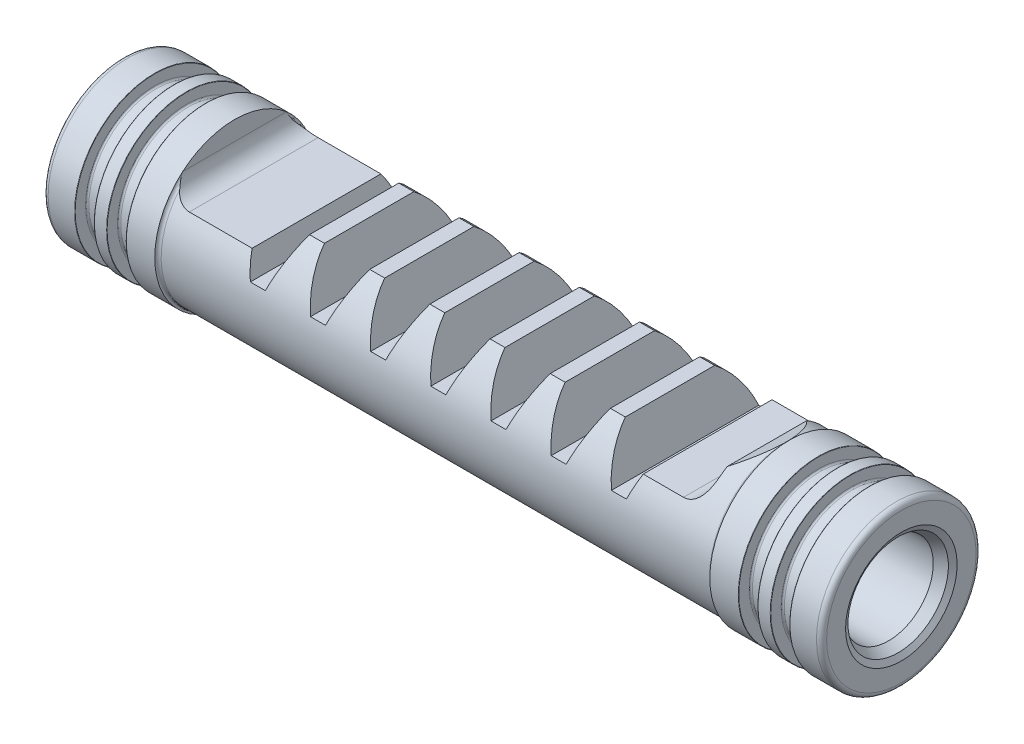
SolidWorks part; units mm, degrees
material "Простая углеродистая сталь"
ref_plane "Спереди" through (0, 0, 0) normal (0, 0, 1) x (1, 0, 0)
ref_plane "Сверху" through (0, 0, 0) normal (0, 1, 0) x (1, 0, 0)
ref_plane "Справа" through (0, 0, 0) normal (1, 0, 0) x (0, 0, -1)
sketch "Эскиз1" plane through (0, 0, 0) normal (0, 0, 1) x (1, 0, 0)
  line L0 (-137.6559, 0) -> (137.6559, 0) construction
  line L1 (-121.94, 17.4641) -> (-121.94, 23.4)
  line L2 (-120.34, 25) -> (-112.04, 25)
  line L3 (-111.94, 24.9) -> (-111.94, 21.65)
  line L4 (-111.44, 21.15) -> (-106.44, 21.15)
  line L5 (-105.94, 21.65) -> (-105.94, 24.9)
  line L6 (-105.84, 25) -> (-102.04, 25)
  line L7 (-101.94, 24.9) -> (-101.94, 21.65)
  line L8 (-101.44, 21.15) -> (-96.44, 21.15)
  line L9 (-95.94, 21.65) -> (-95.94, 24.9)
  line L10 (-95.84, 25) -> (-86.94, 25)
  line L11 (0, 34.36) -> (0, 0) construction
  line L12 (-121.94, 17.4641) -> (-120.94, 15.7321)
  line L13 (-120.94, 15.7321) -> (-117.94, 14)
  line L14 (-117.94, 14) -> (-93.94, 14)
  line L15 (-93.94, 14) -> (-85.8571, 0)
  line L16 (-85.8571, 0) -> (85.8571, 0)
  line L17 (-51.84, 25) -> (-51.84, 0) construction
  line L18 (51.84, 25) -> (51.84, 0) construction
  line L19 (93.94, 14) -> (85.8571, 0)
  line L20 (117.94, 14) -> (93.94, 14)
  line L21 (120.94, 15.7321) -> (117.94, 14)
  line L22 (121.94, 17.4641) -> (120.94, 15.7321)
  line L23 (95.94, 21.65) -> (95.94, 24.9)
  line L24 (101.44, 21.15) -> (96.44, 21.15)
  line L25 (101.94, 24.9) -> (101.94, 21.65)
  line L26 (105.84, 25) -> (102.04, 25)
  line L27 (105.94, 21.65) -> (105.94, 24.9)
  line L28 (111.44, 21.15) -> (106.44, 21.15)
  line L29 (111.94, 24.9) -> (111.94, 21.65)
  line L30 (120.34, 25) -> (112.04, 25)
  line L31 (121.94, 17.4641) -> (121.94, 23.4)
  line L32 (-85.94, 24) -> (85.94, 24)
  line L33 (86.94, 25) -> (95.84, 25)
  arc A0 (-95.94, 24.9) -> (-95.84, 25) centre (-95.84, 24.9) cw
  arc A1 (-102.04, 25) -> (-101.94, 24.9) centre (-102.04, 24.9) cw
  arc A2 (-105.94, 24.9) -> (-105.84, 25) centre (-105.84, 24.9) cw
  arc A3 (-112.04, 25) -> (-111.94, 24.9) centre (-112.04, 24.9) cw
  arc A4 (-96.44, 21.15) -> (-95.94, 21.65) centre (-96.44, 21.65) ccw
  arc A5 (-101.94, 21.65) -> (-101.44, 21.15) centre (-101.44, 21.65) ccw
  arc A6 (-106.44, 21.15) -> (-105.94, 21.65) centre (-106.44, 21.65) ccw
  arc A7 (-111.94, 21.65) -> (-111.44, 21.15) centre (-111.44, 21.65) ccw
  arc A8 (-121.94, 23.4) -> (-120.34, 25) centre (-120.34, 23.4) cw
  arc A9 (121.94, 23.4) -> (120.34, 25) centre (120.34, 23.4) ccw
  arc A10 (111.94, 21.65) -> (111.44, 21.15) centre (111.44, 21.65) cw
  arc A11 (106.44, 21.15) -> (105.94, 21.65) centre (106.44, 21.65) cw
  arc A12 (101.94, 21.65) -> (101.44, 21.15) centre (101.44, 21.65) cw
  arc A13 (96.44, 21.15) -> (95.94, 21.65) centre (96.44, 21.65) cw
  arc A14 (112.04, 25) -> (111.94, 24.9) centre (112.04, 24.9) ccw
  arc A15 (105.94, 24.9) -> (105.84, 25) centre (105.84, 24.9) ccw
  arc A16 (102.04, 25) -> (101.94, 24.9) centre (102.04, 24.9) ccw
  arc A17 (95.94, 24.9) -> (95.84, 25) centre (95.84, 24.9) ccw
  arc A18 (-85.94, 24) -> (-86.94, 25) centre (-85.94, 25) cw
  arc A19 (85.94, 24) -> (86.94, 25) centre (85.94, 25) ccw
  point P74 (0, 25)
  point P82 (0, 24)
  dimension "D3" = 0.1
  dimension "D4" = 0.5
  dimension "D5" = 1.6
  dimension "D19" = 1
  dimension "D1" = 6
  dimension "D2" = 6
  dimension "D6" = 60
  dimension "D7" = 28
  dimension "D8" = 60
  dimension "D9" = 28
  dimension "D10" = 30
  dimension "D11" = 4
  dimension "D12" = 1
  dimension "D13" = 70.1
  dimension "D14" = 103.68
  dimension "D15" = 50
  dimension "D16" = 42.3
  dimension "D17" = 10
  dimension "D18" = 20
  dimension "D20" = 48
  dimension "D21" = 35
revolve "Повернуть1" add sketch "Эскиз1" angle 360 about L0
sketch "Эскиз3" plane through (0, 0, 0) normal (0, 0, 1) x (1, 0, 0)
  line L0 (-86.94, 25) -> (-86.94, 19)
  line L1 (-80.94, 13) -> (-51.84, 13)
  line L2 (-51.84, 13) -> (-51.84, 19.5)
  line L3 (-51.84, 19.5) -> (51.84, 19.5)
  line L4 (51.84, 19.5) -> (51.84, 13)
  line L5 (51.84, 13) -> (73.8778, 13)
  line L6 (79.8778, 20.5) -> (85.94, 24)
  line L7 (85.94, 24) -> (-85.94, 24) construction
  line L8 (85.94, 24) -> (85.94, 25)
  line L9 (85.94, 25) -> (-86.94, 25)
  line L10 (79.8778, 20.5) -> (79.8778, 19)
  line L11 (-51.84, 25) -> (-51.84, 0) construction
  line L12 (51.84, 25) -> (51.84, 0) construction
  line L13 (-95.84, -25) -> (-86.94, -25) construction
  arc A0 (73.8778, 13) -> (79.8778, 19) centre (73.8778, 19) ccw
  arc A1 (-86.94, 19) -> (-80.94, 13) centre (-80.94, 19) ccw
  dimension "D2" = 12
  dimension "D4" = 6
  dimension "D1" = 3.5
  dimension "D3" = 44.5
  dimension "D5" = 30
extrude "Вырез-Вытянуть1" cut sketch "Эскиз3" against normal through all and the other way through all
sketch "Эскиз5" plane through (0, 0, 0) normal (0, 0, 1) x (1, 0, 0)
  line L0 (-48.3517, -24) -> (-39.64, -17.9)
  line L1 (-85.94, -24) -> (85.94, -24) construction
  line L2 (-39.64, -17.9) -> (-24.64, -17.9)
  line L3 (-24.64, -17.9) -> (-14.7491, -21.5)
  line L4 (-14.7491, -21.5) -> (91.94, -21.5)
  line L5 (91.94, -21.5) -> (91.94, -24)
  line L6 (86.94, -25) -> (95.84, -25) construction
  line L7 (92.94, -25) -> (-48.3517, -25)
  line L8 (-48.3517, -25) -> (-48.3517, -24)
  line L9 (-121.94, 23.4) -> (-121.94, -23.4) construction
  line L10 (121.94, -23.4) -> (121.94, 23.4) construction
  arc A0 (91.94, -24) -> (92.94, -25) centre (92.94, -24) ccw
  dimension "D8" = 1
  dimension "D1" = 35
  dimension "D2" = 3.6
  dimension "D3" = 7.1
  dimension "D4" = 15
  dimension "D5" = 20
  dimension "D6" = 97.3
  dimension "D7" = 30
extrude "Вырез-Вытянуть3" cut sketch "Эскиз5" against normal through all and the other way through all
sketch "Эскиз4" plane through (0, 0, 0) normal (0, 0, 1) x (1, 0, 0)
  line L0 (-54.2058, 6.5) -> (-49.4742, 19.5)
  line L1 (-49.4742, 19.5) -> (-63.6308, 19.5)
  line L2 (-63.6308, 19.5) -> (-58.8992, 6.5)
  line L3 (-58.8992, 6.5) -> (-54.2058, 6.5)
  line L4 (51.84, 19.5) -> (-51.84, 19.5) construction
  line L5 (-61.265, 13) -> (-51.84, 13) construction
  line L6 (-51.84, 13) -> (-80.94, 13) construction
  dimension "D1" = 9.425
  dimension "D2" = 40
extrude "Вырез-Вытянуть2" cut sketch "Эскиз4" against normal through all and the other way through all
pattern_linear "Линейный массив1" count 7 spacing 18.85 along (1, 0, 0) of "Вырез-Вытянуть2"
